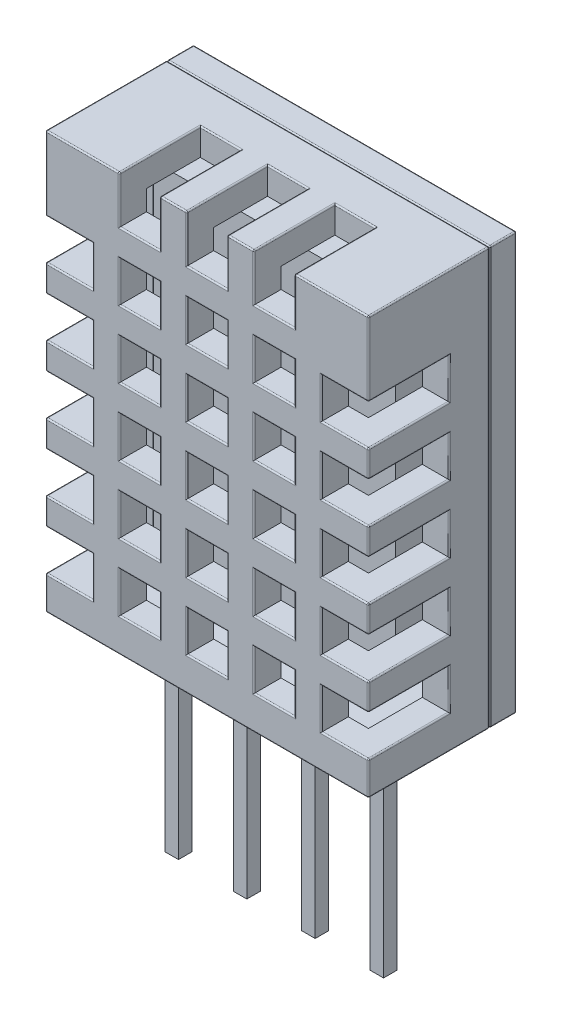
SolidWorks part; units mm, degrees
ref_plane "Front Plane" through (0, 0, 0) normal (0, 0, 1) x (1, 0, 0)
ref_plane "Top Plane" through (0, 0, 0) normal (0, 1, 0) x (1, 0, 0)
ref_plane "Right Plane" through (0, 0, 0) normal (1, 0, 0) x (0, 0, -1)
sketch "Sketch1" plane through (0, 0, 0) normal (0, 0, 1) x (1, 0, 0)
  line L1 (0, 0) -> (12, 0)
  line L2 (0, 0) -> (0, 15.5)
  line L3 (0, 15.5) -> (12, 15.5)
  line L4 (12, 0) -> (12, 15.5)
  dimension "D1" = 12
  dimension "D2" = 15.5
extrude "Boss-Extrude1" add sketch "Sketch1" along normal blind 5.5
sketch "Sketch2" plane through (0, 0, 0) normal (0, -1, 0) x (1, 0, 0)
  line L0 (0, 5.5) -> (0, 0) construction
  line L1 (1.94, 3) -> (2.44, 3)
  line L2 (1.94, 3) -> (1.94, 2.5)
  line L3 (1.94, 2.5) -> (2.44, 2.5)
  line L4 (2.44, 3) -> (2.44, 2.5)
  line L5 (0, 2.75) -> (12, 2.75) construction
  line L6 (12, 5.5) -> (12, 0) construction
  line L7 (4.48, 3) -> (4.98, 3)
  line L8 (4.48, 3) -> (4.48, 2.5)
  line L9 (4.48, 2.5) -> (4.98, 2.5)
  line L10 (4.98, 3) -> (4.98, 2.5)
  line L11 (7.02, 3) -> (7.52, 3)
  line L12 (7.02, 3) -> (7.02, 2.5)
  line L13 (7.02, 2.5) -> (7.52, 2.5)
  line L14 (7.52, 3) -> (7.52, 2.5)
  line L15 (9.56, 3) -> (10.06, 3)
  line L16 (9.56, 3) -> (9.56, 2.5)
  line L17 (9.56, 2.5) -> (10.06, 2.5)
  line L18 (10.06, 3) -> (10.06, 2.5)
  point P11 (1.94, 2.75)
  dimension "D1" = 0.5
  dimension "D2" = 0.5
  dimension "D3" = 1.94
  dimension "D4" = 4
extrude "Boss-Extrude2" add sketch "Sketch2" along normal blind 8
shell "Shell2" thickness 1
sketch "Sketch3" plane through (0, 0, 5.5) normal (0, 0, 1) x (1, 0, 0)
  line L0 (12, 15.5) -> (0, 15.5) construction
  line L1 (2.75, 15.5) -> (4.25, 15.5)
  line L2 (2.75, 15.5) -> (2.75, 13.75)
  line L3 (2.75, 13.75) -> (4.25, 13.75)
  line L4 (4.25, 15.5) -> (4.25, 13.75)
  line L5 (5.25, 15.5) -> (6.75, 15.5)
  line L6 (5.25, 15.5) -> (5.25, 13.75)
  line L7 (5.25, 13.75) -> (6.75, 13.75)
  line L8 (6.75, 15.5) -> (6.75, 13.75)
  line L9 (7.75, 15.5) -> (9.25, 15.5)
  line L10 (7.75, 15.5) -> (7.75, 13.75)
  line L11 (7.75, 13.75) -> (9.25, 13.75)
  line L12 (9.25, 15.5) -> (9.25, 13.75)
  line L13 (0, 15.5) -> (0, 0) construction
  dimension "D1" = 1.5
  dimension "D2" = 1.75
  dimension "D4" = 2.75
  dimension "D3" = 3
extrude "Cut-Extrude1" cut sketch "Sketch3" against normal blind 3
sketch "Sketch4" plane through (0, 0, 5.5) normal (0, 0, 1) x (1, 0, 0)
  line L0 (2.75, 13.75) -> (4.25, 13.75) construction
  line L1 (2.75, 12.75) -> (4.25, 12.75)
  line L2 (2.75, 12.75) -> (2.75, 11.25)
  line L3 (2.75, 11.25) -> (4.25, 11.25)
  line L4 (4.25, 12.75) -> (4.25, 11.25)
  line L5 (0, 15.5) -> (0, 0) construction
  line L6 (5.25, 12.75) -> (6.75, 12.75)
  line L7 (5.25, 12.75) -> (5.25, 11.25)
  line L8 (5.25, 11.25) -> (6.75, 11.25)
  line L9 (6.75, 12.75) -> (6.75, 11.25)
  line L10 (7.75, 12.75) -> (9.25, 12.75)
  line L11 (7.75, 12.75) -> (7.75, 11.25)
  line L12 (7.75, 11.25) -> (9.25, 11.25)
  line L13 (9.25, 12.75) -> (9.25, 11.25)
  line L14 (5.25, 10.25) -> (6.75, 10.25)
  line L15 (5.25, 10.25) -> (5.25, 8.75)
  line L16 (5.25, 8.75) -> (6.75, 8.75)
  line L17 (6.75, 10.25) -> (6.75, 8.75)
  line L18 (7.75, 10.25) -> (9.25, 10.25)
  line L19 (7.75, 10.25) -> (7.75, 8.75)
  line L20 (7.75, 8.75) -> (9.25, 8.75)
  line L21 (9.25, 10.25) -> (9.25, 8.75)
  line L22 (5.25, 7.75) -> (6.75, 7.75)
  line L23 (5.25, 7.75) -> (5.25, 6.25)
  line L24 (5.25, 6.25) -> (6.75, 6.25)
  line L25 (6.75, 7.75) -> (6.75, 6.25)
  line L26 (7.75, 7.75) -> (9.25, 7.75)
  line L27 (7.75, 7.75) -> (7.75, 6.25)
  line L28 (7.75, 6.25) -> (9.25, 6.25)
  line L29 (9.25, 7.75) -> (9.25, 6.25)
  line L30 (5.25, 5.25) -> (6.75, 5.25)
  line L31 (5.25, 5.25) -> (5.25, 3.75)
  line L32 (5.25, 3.75) -> (6.75, 3.75)
  line L33 (6.75, 5.25) -> (6.75, 3.75)
  line L34 (7.75, 5.25) -> (9.25, 5.25)
  line L35 (7.75, 5.25) -> (7.75, 3.75)
  line L36 (7.75, 3.75) -> (9.25, 3.75)
  line L37 (9.25, 5.25) -> (9.25, 3.75)
  line L38 (5.25, 2.75) -> (6.75, 2.75)
  line L39 (5.25, 2.75) -> (5.25, 1.25)
  line L40 (5.25, 1.25) -> (6.75, 1.25)
  line L41 (6.75, 2.75) -> (6.75, 1.25)
  line L42 (7.75, 2.75) -> (9.25, 2.75)
  line L43 (7.75, 2.75) -> (7.75, 1.25)
  line L44 (7.75, 1.25) -> (9.25, 1.25)
  line L45 (9.25, 2.75) -> (9.25, 1.25)
  line L46 (2.75, 10.25) -> (4.25, 10.25)
  line L47 (2.75, 10.25) -> (2.75, 8.75)
  line L48 (2.75, 8.75) -> (4.25, 8.75)
  line L49 (4.25, 10.25) -> (4.25, 8.75)
  line L50 (2.75, 7.75) -> (4.25, 7.75)
  line L51 (2.75, 7.75) -> (2.75, 6.25)
  line L52 (2.75, 6.25) -> (4.25, 6.25)
  line L53 (4.25, 7.75) -> (4.25, 6.25)
  line L54 (2.75, 5.25) -> (4.25, 5.25)
  line L55 (2.75, 5.25) -> (2.75, 3.75)
  line L56 (2.75, 3.75) -> (4.25, 3.75)
  line L57 (4.25, 5.25) -> (4.25, 3.75)
  line L58 (2.75, 2.75) -> (4.25, 2.75)
  line L59 (2.75, 2.75) -> (2.75, 1.25)
  line L60 (2.75, 1.25) -> (4.25, 1.25)
  line L61 (4.25, 2.75) -> (4.25, 1.25)
  dimension "D1" = 1.5
  dimension "D2" = 1
  dimension "D3" = 2.75
  dimension "D4" = 3
  dimension "D5" = 5
extrude "Cut-Extrude2" cut sketch "Sketch4" against normal blind 3
sketch "Sketch5" plane through (0, 0, 5.5) normal (0, 0, 1) x (1, 0, 0)
  line L0 (0, 15.5) -> (0, 0) construction
  line L1 (0, 12.75) -> (1.75, 12.75)
  line L2 (0, 12.75) -> (0, 11.25)
  line L3 (0, 11.25) -> (1.75, 11.25)
  line L4 (1.75, 12.75) -> (1.75, 11.25)
  line L7 (2.75, 12.75) -> (2.75, 11.25) construction
  line L8 (10.25, 12.75) -> (12, 12.75)
  line L9 (10.25, 12.75) -> (10.25, 11.25)
  line L10 (10.25, 11.25) -> (12, 11.25)
  line L11 (12, 12.75) -> (12, 11.25)
  line L12 (10.25, 10.25) -> (12, 10.25)
  line L13 (10.25, 10.25) -> (10.25, 8.75)
  line L14 (10.25, 8.75) -> (12, 8.75)
  line L15 (12, 10.25) -> (12, 8.75)
  line L16 (10.25, 7.75) -> (12, 7.75)
  line L17 (10.25, 7.75) -> (10.25, 6.25)
  line L18 (10.25, 6.25) -> (12, 6.25)
  line L19 (12, 7.75) -> (12, 6.25)
  line L20 (10.25, 5.25) -> (12, 5.25)
  line L21 (10.25, 5.25) -> (10.25, 3.75)
  line L22 (10.25, 3.75) -> (12, 3.75)
  line L23 (12, 5.25) -> (12, 3.75)
  line L24 (10.25, 2.75) -> (12, 2.75)
  line L25 (10.25, 2.75) -> (10.25, 1.25)
  line L26 (10.25, 1.25) -> (12, 1.25)
  line L27 (12, 2.75) -> (12, 1.25)
  line L28 (0, 10.25) -> (1.75, 10.25)
  line L29 (0, 10.25) -> (0, 8.75)
  line L30 (0, 8.75) -> (1.75, 8.75)
  line L31 (1.75, 10.25) -> (1.75, 8.75)
  line L32 (0, 7.75) -> (1.75, 7.75)
  line L33 (0, 7.75) -> (0, 6.25)
  line L34 (0, 6.25) -> (1.75, 6.25)
  line L35 (1.75, 7.75) -> (1.75, 6.25)
  line L36 (0, 5.25) -> (1.75, 5.25)
  line L37 (0, 5.25) -> (0, 3.75)
  line L38 (0, 3.75) -> (1.75, 3.75)
  line L39 (1.75, 5.25) -> (1.75, 3.75)
  line L40 (0, 2.75) -> (1.75, 2.75)
  line L41 (0, 2.75) -> (0, 1.25)
  line L42 (0, 1.25) -> (1.75, 1.25)
  line L43 (1.75, 2.75) -> (1.75, 1.25)
  dimension "D1" = 1
  dimension "D2" = 2
  dimension "D3" = 5
extrude "Cut-Extrude3" cut sketch "Sketch5" against normal blind 3
sketch "Sketch6" plane through (0, 0, 0) normal (0, 0, -1) x (-1, 0, 0)
  line L4 (0, 0) -> (0, 15.5)
  line L5 (0, 15.5) -> (-12, 15.5)
  line L6 (-12, 15.5) -> (-12, 0)
  line L7 (-12, 0) -> (0, 0)
  line L8 (0, 0) -> (0, 15.5)
  line L9 (0, 15.5) -> (-12, 15.5)
  line L10 (-12, 15.5) -> (-12, 0)
  line L11 (-12, 0) -> (0, 0)
  line L12 (-1, 14.5) -> (-11, 14.5)
  line L13 (-1, 1) -> (-1, 14.5)
  line L14 (-11, 1) -> (-1, 1)
  line L15 (-11, 14.5) -> (-11, 1)
  line L16 (-1, 14.5) -> (-11, 14.5)
  line L17 (-1, 1) -> (-1, 14.5)
  line L18 (-11, 1) -> (-1, 1)
  line L19 (-11, 14.5) -> (-11, 1)
  dimension "D1" = 0
  dimension "D2" = 0
extrude "Cut-Extrude4" cut sketch "Sketch6" against normal blind 1
ref_plane "Plane1" through (0, 0, 0.99) normal (0, 0, 1) x (1, 0, 0)
sketch "Sketch8" plane through (0, 0, 0.99) normal (0, 0, 1) x (1, 0, 0)
  line L4 (0, 0) -> (12, 0)
  line L5 (0, 15.5) -> (0, 0)
  line L6 (12, 15.5) -> (0, 15.5)
  line L7 (12, 0) -> (12, 15.5)
  line L8 (0, 0) -> (12, 0)
  line L9 (0, 15.5) -> (0, 0)
  line L10 (12, 15.5) -> (0, 15.5)
  line L11 (12, 0) -> (12, 15.5)
  dimension "D1" = 0
extrude "Boss-Extrude3" add sketch "Sketch8" against normal blind 0.99 separate body
sketch "Sketch9" plane through (0, 0, 0) normal (0, -1, 0) x (1, 0, 0)
  line L0 (1.94, 3) -> (1.94, 2.5) construction
  line L1 (1.94, 2.5) -> (2.44, 2.5) construction
  line L2 (2.44, 2.5) -> (2.44, 3) construction
  line L3 (2.44, 3) -> (1.94, 3) construction
  line L4 (4.48, 3) -> (4.48, 2.5) construction
  line L5 (4.48, 2.5) -> (4.98, 2.5) construction
  line L6 (4.98, 2.5) -> (4.98, 3) construction
  line L7 (4.98, 3) -> (4.48, 3) construction
  line L8 (7.02, 3) -> (7.02, 2.5) construction
  line L9 (7.02, 2.5) -> (7.52, 2.5) construction
  line L10 (7.52, 2.5) -> (7.52, 3) construction
  line L11 (7.52, 3) -> (7.02, 3) construction
  line L12 (9.56, 3) -> (9.56, 2.5) construction
  line L13 (9.56, 2.5) -> (10.06, 2.5) construction
  line L14 (10.06, 2.5) -> (10.06, 3) construction
  line L15 (10.06, 3) -> (9.56, 3) construction
  line L16 (1.94, 3) -> (1.94, 2.5)
  line L17 (1.94, 2.5) -> (2.44, 2.5)
  line L18 (2.44, 2.5) -> (2.44, 3)
  line L19 (2.44, 3) -> (1.94, 3)
  line L20 (4.48, 3) -> (4.48, 2.5)
  line L21 (4.48, 2.5) -> (4.98, 2.5)
  line L22 (4.98, 2.5) -> (4.98, 3)
  line L23 (4.98, 3) -> (4.48, 3)
  line L24 (7.02, 3) -> (7.02, 2.5)
  line L25 (7.02, 2.5) -> (7.52, 2.5)
  line L26 (7.52, 2.5) -> (7.52, 3)
  line L27 (7.52, 3) -> (7.02, 3)
  line L28 (9.56, 3) -> (9.56, 2.5)
  line L29 (9.56, 2.5) -> (10.06, 2.5)
  line L30 (10.06, 2.5) -> (10.06, 3)
  line L31 (10.06, 3) -> (9.56, 3)
  line L32 (1.84, 3.1) -> (1.84, 2.4)
  line L33 (1.84, 2.4) -> (2.54, 2.4)
  line L34 (2.54, 2.4) -> (2.54, 3.1)
  line L35 (2.54, 3.1) -> (1.84, 3.1)
  line L36 (4.38, 3.1) -> (4.38, 2.4)
  line L37 (4.38, 2.4) -> (5.08, 2.4)
  line L38 (5.08, 2.4) -> (5.08, 3.1)
  line L39 (5.08, 3.1) -> (4.38, 3.1)
  line L40 (6.92, 3.1) -> (6.92, 2.4)
  line L41 (6.92, 2.4) -> (7.62, 2.4)
  line L42 (7.62, 2.4) -> (7.62, 3.1)
  line L43 (7.62, 3.1) -> (6.92, 3.1)
  line L44 (9.46, 3.1) -> (9.46, 2.4)
  line L45 (9.46, 2.4) -> (10.16, 2.4)
  line L46 (10.16, 2.4) -> (10.16, 3.1)
  line L47 (10.16, 3.1) -> (9.46, 3.1)
  dimension "D1" = 0.1
extrude "Cut-Extrude5" cut sketch "Sketch9" against normal blind 1
fillet "Fillet1" radius 0.05 106 edges at (6, 0, 1) (2.54, 0, 2.75) (4.73, 0, 2.4) (5.08, 0, 2.75) (4.73, 0, 3.1) (7.27, 0, 2.4) (7.62, 0, 2.75) (7.27, 0, 3.1) (6.92, 0, 2.75) (9.81, 0, 2.4) (10.16, 0, 2.75) (0, 12.75, 4) (0, 12, 2.5) (0, 11.25, 4) (0, 10.25, 4) (0, 9.5, 2.5) (0, 7.75, 4) (0, 7, 2.5) (0, 6.25, 4) (0, 5.25, 4) (0, 2.75, 4) (0, 2, 2.5) (0, 0, 3.25) (9.25, 15.5, 4) (8.5, 15.5, 2.5) (7.75, 15.5, 4) (6.75, 15.5, 4) (6, 15.5, 2.5) (5.25, 15.5, 4) (4.25, 15.5, 4) (3.5, 15.5, 2.5) (2.75, 15.5, 4) (0, 15.5, 3.25) (6, 15.5, 1) (12, 1.25, 4) (12, 2, 2.5) (12, 3.75, 4) (12, 5.25, 4) (12, 6.25, 4) (12, 7.75, 4) (12, 8.75, 4) (12, 10.25, 4) (12, 11.25, 4) (12, 12, 2.5) (12, 7.75, 1) (0.875, 3.75, 5.5) (1.75, 4.5, 5.5) (0.875, 5.25, 5.5) (0, 5.75, 5.5) (0.875, 6.25, 5.5) (1.75, 7, 5.5) (0, 10.75, 5.5) (0.875, 11.25, 5.5) (0.875, 12.75, 5.5) (0, 14.125, 5.5) (1.375, 15.5, 5.5) (2.75, 14.625, 5.5) (4.25, 14.625, 5.5) (6.75, 14.625, 5.5) (7.75, 14.625, 5.5) (8.5, 13.75, 5.5) (10.625, 15.5, 5.5) (12, 14.125, 5.5) (11.125, 12.75, 5.5) (10.25, 12, 5.5) (12, 10.75, 5.5) (11.125, 10.25, 5.5) (11.125, 8.75, 5.5) (10.25, 7, 5.5) (11.125, 6.25, 5.5) (12, 5.75, 5.5) (11.125, 2.75, 5.5) (10.25, 2, 5.5) (11.125, 1.25, 5.5) (0, 0.625, 5.5) (1.75, 2, 5.5) (2.75, 12, 5.5) (6.75, 12, 5.5) (6, 12.75, 5.5) (6, 11.25, 5.5) (9.25, 12, 5.5) (7.75, 12, 5.5) (6.75, 9.5, 5.5) (6, 10.25, 5.5) (6, 8.75, 5.5) (9.25, 9.5, 5.5) (8.5, 10.25, 5.5) (7.75, 9.5, 5.5) (6.75, 7, 5.5) (6, 7.75, 5.5) (6, 6.25, 5.5) (9.25, 7, 5.5) (6.75, 4.5, 5.5) (6, 5.25, 5.5) (6, 3.75, 5.5) (9.25, 4.5, 5.5) (6, 2.75, 5.5) (5.25, 2, 5.5) (8.5, 1.25, 5.5) (4.25, 9.5, 5.5) (3.5, 7.75, 5.5) (2.75, 7, 5.5) (4.25, 4.5, 5.5) (2.75, 4.5, 5.5) (4.25, 2, 5.5) (2.75, 2, 5.5)
fillet "Fillet2" radius 0.05 12 edges at (6, 15.5, 0.99) (0, 15.5, 0.495) (0, 7.75, 0.99) (0, 0, 0.495) (6, 0, 0.99) (12, 15.5, 0.495) (12, 0, 0.495) (12, 7.75, 0.99) (6, 15.5, 0) (0, 7.75, 0) (6, 0, 0) (12, 7.75, 0)
sketch "Sketch10" plane through (0, 0, 0.99) normal (0, 0, 1) x (1, 0, 0)
  line L14 (1.5, 1.5) -> (10.5, 1.5)
  line L15 (10.5, 1.5) -> (10.5, 14)
  line L16 (10.5, 14) -> (1.5, 14)
  line L17 (1.5, 14) -> (1.5, 1.5)
  line L18 (1.5, 1.5) -> (10.5, 1.5)
  line L19 (10.5, 1.5) -> (10.5, 14)
  line L20 (10.5, 14) -> (1.5, 14)
  line L21 (1.5, 14) -> (1.5, 1.5)
  dimension "D1" = 0.5
extrude "Boss-Extrude4" add sketch "Sketch10" along normal blind 2
